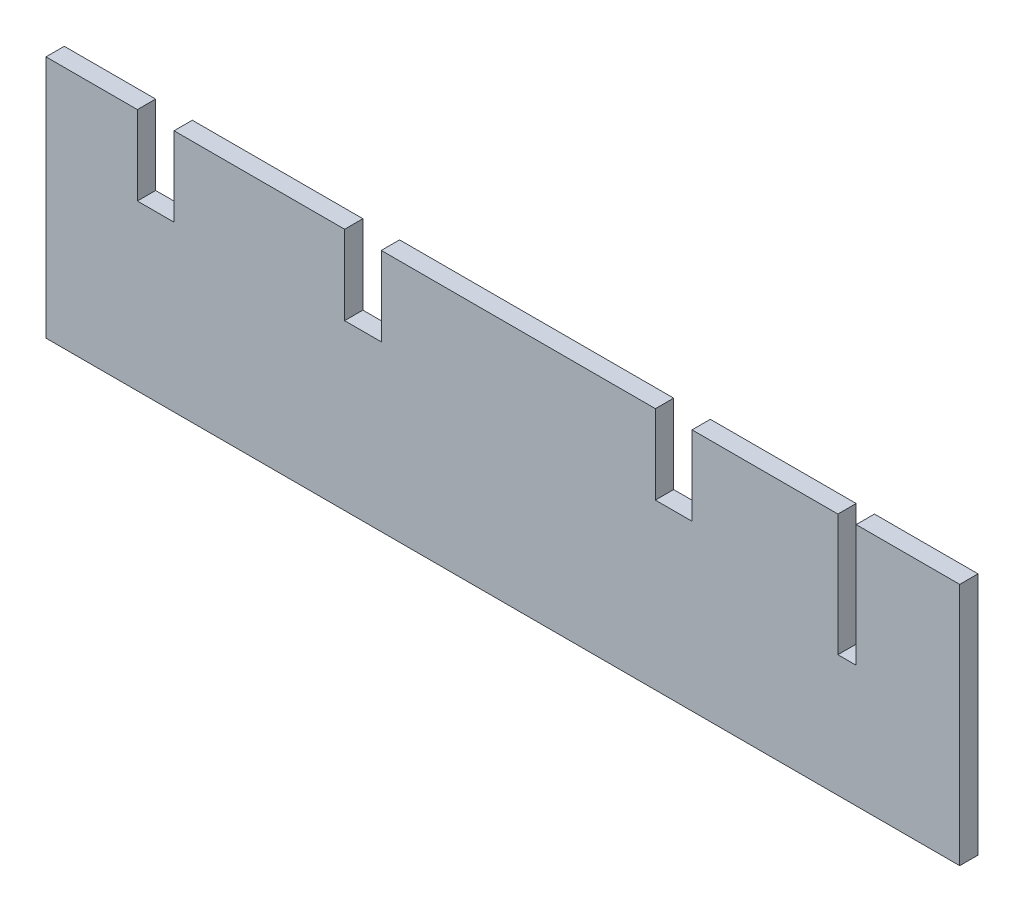
SolidWorks part; units mm, degrees
ref_plane "Front Plane" through (0, 0, 0) normal (0, 0, 1) x (1, 0, 0)
ref_plane "Top Plane" through (0, 0, 0) normal (0, 1, 0) x (1, 0, 0)
ref_plane "Right Plane" through (0, 0, 0) normal (1, 0, 0) x (0, 0, -1)
sketch "Sketch1" plane through (0, 0, 0) normal (0, 0, 1) x (1, 0, 0)
  line L0 (-350, 40) -> (-350, 14)
  line L1 (-380, 40) -> (-350, 40)
  line L2 (-380, 40) -> (-380, -40)
  line L3 (-380, -40) -> (-80, -40)
  line L5 (-380, 40) -> (380, -40) construction
  line L7 (-281.96, 14) -> (-269.92, 14)
  line L9 (-337.96, 14) -> (-337.96, 40)
  line L10 (-281.96, 14) -> (-281.96, 40)
  line L11 (-269.92, 14) -> (-269.92, 40)
  line L12 (-179.92, 14) -> (-179.92, 40)
  line L17 (-167.88, 14) -> (-167.88, 40)
  line L18 (-350, 14) -> (-337.96, 14)
  line L19 (-337.96, 40) -> (-281.96, 40)
  line L20 (-269.92, 40) -> (-179.92, 40)
  line L21 (-167.88, 40) -> (-80, 40)
  line L22 (-179.92, 14) -> (-167.88, 14)
  line L28 (-80, 40) -> (-80, -40)
  point P0 (0, 0)
  dimension "D1" = 80
  dimension "D2" = 760
  dimension "D3" = 54
  dimension "D4" = 30
  dimension "D5" = 12.04
  dimension "D6" = 56
  dimension "D7" = 12.04
  dimension "D8" = 90
  dimension "D9" = 12.04
  dimension "D18" = 300
extrude "Boss-Extrude1" add sketch "Sketch1" along normal blind 6
sketch "Sketch2" plane through (0, 0, 0) normal (0, 0, -1) x (-1, 0, 0)
  line L5 (54, 0) -> (60, 0)
  line L15 (54, 0) -> (54, 40)
  line L16 (80, 40) -> (167.88, 40) construction
  line L17 (54, 40) -> (60, 40)
  line L18 (60, 40) -> (60, 0)
  line L20 (380, 40) -> (380, -40) construction
  line L25 (114, 40) -> (120, 40)
  line L26 (114, 40) -> (114, 0)
  line L27 (114, 0) -> (120, 0)
  line L28 (120, 40) -> (120, 0)
  dimension "D3" = 6
  dimension "D5" = 320
  dimension "D7" = 6
  dimension "D9" = 40
  dimension "D11" = 260
extrude "Cut-Extrude1" cut sketch "Sketch2" against normal blind 10
